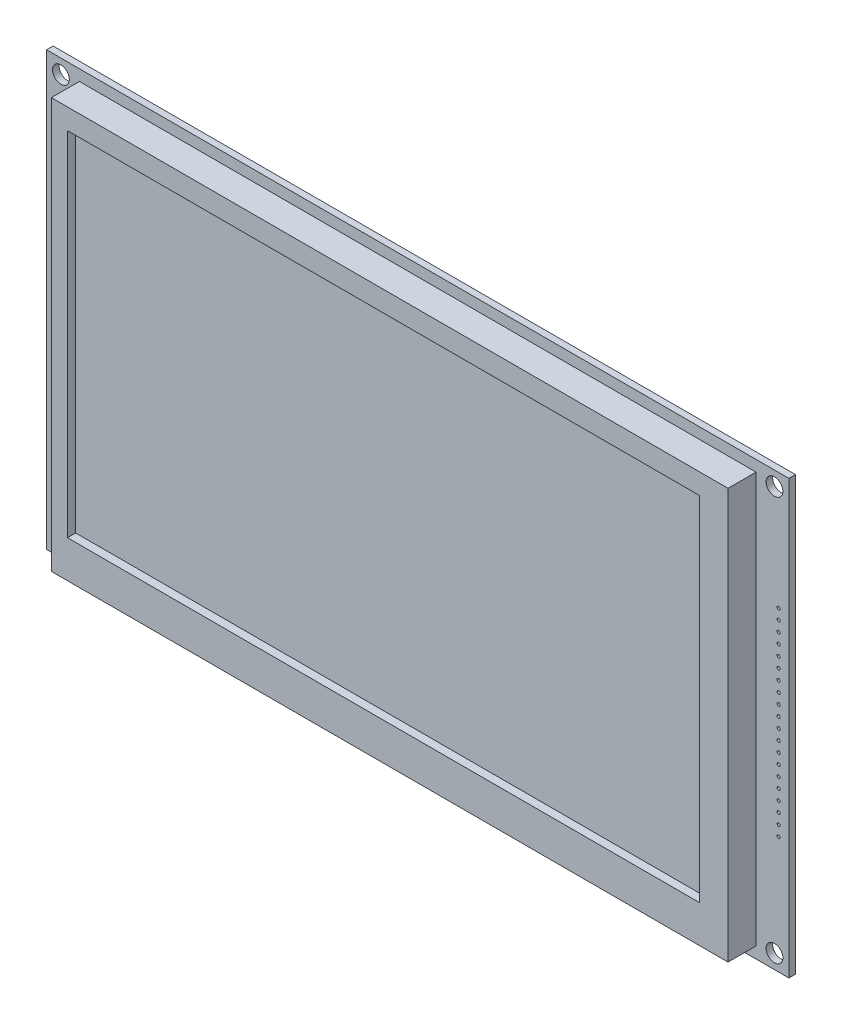
SolidWorks part; units mm, degrees
material "Custom Plastic"
ref_plane "Front Plane" through (0, 0, 0) normal (0, 0, 1) x (1, 0, 0)
ref_plane "Top Plane" through (0, 0, 0) normal (0, 1, 0) x (1, 0, 0)
ref_plane "Right Plane" through (0, 0, 0) normal (1, 0, 0) x (0, 0, -1)
sketch "Sketch1" plane through (0, 0, 0) normal (0, 0, 1) x (1, 0, 0)
  line L1 (90.45, -52.725) -> (-90.45, -52.725)
  line L2 (90.45, -52.725) -> (90.45, 52.725)
  line L3 (90.45, 52.725) -> (-90.45, 52.725)
  line L4 (-90.45, -52.725) -> (-90.45, 52.725)
  line L5 (90.45, -52.725) -> (-90.45, 52.725) construction
  line L6 (90.45, 52.725) -> (-90.45, -52.725) construction
  circle A0 centre (86.95, 49.245) radius 2.05
  circle A1 centre (-86.96, 49.245) radius 2.05
  circle A2 centre (-86.96, -49.225) radius 2.05
  circle A3 centre (86.95, -49.225) radius 2.05
  point P0 (0, 0)
  dimension "D3" = 4.1
  dimension "D4" = 3.5
  dimension "D7" = 3.48
  dimension "D8" = 98.47
  dimension "D1" = 105.45
  dimension "D2" = 180.9
  dimension "D6" = 173.91
extrude "Boss-Extrude1" add sketch "Sketch1" along normal mid plane 1.6
sketch "Sketch2" plane through (0, 0, 0.8) normal (0, 0, 1) x (1, 0, 0)
  line L0 (90.45, 52.725) -> (-90.45, 52.725) construction
  line L1 (-82.45, 50.045) -> (82.45, 50.045)
  line L2 (-82.45, 50.045) -> (-82.45, -49.955)
  line L3 (-82.45, -49.955) -> (82.45, -49.955)
  line L4 (82.45, 50.045) -> (82.45, -49.955)
  line L5 (90.45, -52.725) -> (90.45, 52.725) construction
  dimension "D1" = 164.9
  dimension "D2" = 100
  dimension "D3" = 2.68
  dimension "D4" = 8
extrude "Boss-Extrude2" add sketch "Sketch2" along normal blind 6.83
sketch "Sketch3" plane through (0, -52.725, 0) normal (0, -1, 0) x (1, 0, 0)
  line L0 (17.37, -0.8) -> (23.15, -0.8)
  line L1 (-0.91, -0.8) -> (4.87, -0.8)
  line L2 (-2.49, -2.38) -> (-2.49, -2.48)
  line L3 (-0.91, -4.06) -> (4.87, -4.06)
  line L4 (6.45, -2.38) -> (6.45, -2.48)
  line L5 (15.79, -2.38) -> (15.79, -2.48)
  line L6 (17.37, -4.06) -> (23.15, -4.06)
  line L7 (24.73, -2.38) -> (24.73, -2.48)
  line L8 (-90.45, -0.8) -> (90.45, -0.8) construction
  line L9 (-90.45, 0.8) -> (-90.45, -0.8) construction
  arc A0 (4.87, -0.8) -> (6.45, -2.38) centre (4.87, -2.38) cw
  arc A1 (4.87, -4.06) -> (6.45, -2.48) centre (4.87, -2.48) ccw
  arc A2 (-2.49, -2.48) -> (-0.91, -4.06) centre (-0.91, -2.48) ccw
  arc A3 (-0.91, -0.8) -> (-2.49, -2.38) centre (-0.91, -2.38) ccw
  arc A4 (15.79, -2.48) -> (17.37, -4.06) centre (17.37, -2.48) ccw
  arc A5 (17.37, -0.8) -> (15.79, -2.38) centre (17.37, -2.38) ccw
  arc A6 (23.15, -0.8) -> (24.73, -2.38) centre (23.15, -2.38) cw
  arc A7 (23.15, -4.06) -> (24.73, -2.48) centre (23.15, -2.48) ccw
  point P14 (1.98, -4.06)
  point P15 (20.26, -4.06)
  point P20 (6.45, -4.06)
  point P23 (-2.49, -4.06)
  point P26 (-2.49, -0.8)
  dimension "D5" = 1.58
  dimension "D1" = 8.94
  dimension "D2" = 3.26
  dimension "D3" = 92.43
  dimension "D4" = 110.71
extrude "Boss-Extrude3" add sketch "Sketch3" against normal blind 11
sketch "Sketch4" plane through (0, 0, -0.8) normal (0, 0, -1) x (-1, 0, 0)
  line L0 (90.45, -52.725) -> (0.91, -52.725) construction
  line L1 (62.92, -52.205) -> (69.92, -52.205)
  line L2 (62.92, -52.205) -> (62.92, -48.205)
  line L3 (62.92, -48.205) -> (69.92, -48.205)
  line L4 (69.92, -52.205) -> (69.92, -48.205)
  line L5 (62.92, -52.205) -> (69.92, -48.205) construction
  line L6 (62.92, -48.205) -> (69.92, -52.205) construction
  line L7 (73.41, -52.205) -> (80.41, -52.205)
  line L8 (73.41, -52.205) -> (73.41, -48.205)
  line L9 (73.41, -48.205) -> (80.41, -48.205)
  line L10 (80.41, -52.205) -> (80.41, -48.205)
  line L11 (73.41, -52.205) -> (80.41, -48.205) construction
  line L12 (73.41, -48.205) -> (80.41, -52.205) construction
  line L13 (90.45, 52.725) -> (90.45, -52.725) construction
  point P0 (66.42, -50.205)
  point P5 (76.91, -50.205)
  dimension "D1" = 7
  dimension "D2" = 2.52
  dimension "D3" = 13.54
  dimension "D4" = 24.03
  dimension "D5" = 4
extrude "Boss-Extrude4" add sketch "Sketch4" along normal blind 1.5
sketch "Sketch5" plane through (0, 0, -0.8) normal (0, 0, -1) x (-1, 0, 0)
  line L5 (90.45, 52.725) -> (90.45, -52.725) construction
  line L6 (-90.45, -52.725) -> (-90.45, 52.725) construction
  circle A0 centre (87.95, 24.125) radius 0.38
  circle A1 centre (86.96, 49.245) radius 2.05 construction
  circle A2 centre (87.95, 21.585) radius 0.38
  circle A3 centre (87.95, 19.045) radius 0.38
  circle A4 centre (87.95, 16.505) radius 0.38
  circle A5 centre (87.95, 13.965) radius 0.38
  circle A6 centre (87.95, 11.425) radius 0.38
  circle A7 centre (87.95, 8.885) radius 0.38
  circle A8 centre (87.95, 6.345) radius 0.38
  circle A9 centre (87.95, 3.805) radius 0.38
  circle A10 centre (87.95, 1.265) radius 0.38
  circle A11 centre (87.95, -1.275) radius 0.38
  circle A12 centre (87.95, -3.815) radius 0.38
  circle A13 centre (87.95, -6.355) radius 0.38
  circle A14 centre (87.95, -8.895) radius 0.38
  circle A15 centre (87.95, -11.435) radius 0.38
  circle A16 centre (87.95, -13.975) radius 0.38
  circle A17 centre (87.95, -16.515) radius 0.38
  circle A18 centre (87.95, -19.055) radius 0.38
  circle A19 centre (87.95, -21.595) radius 0.38
  circle A20 centre (87.95, -24.135) radius 0.38
  circle A21 centre (-87.96, 24.095) radius 0.38
  circle A22 centre (-86.95, 49.245) radius 2.05 construction
  circle A23 centre (-87.96, 21.555) radius 0.38
  circle A24 centre (-87.96, 19.015) radius 0.38
  circle A25 centre (-87.96, 16.475) radius 0.38
  circle A26 centre (-87.96, 13.935) radius 0.38
  circle A27 centre (-87.96, 11.395) radius 0.38
  circle A28 centre (-87.96, 8.855) radius 0.38
  circle A29 centre (-87.96, 6.315) radius 0.38
  circle A30 centre (-87.96, 3.775) radius 0.38
  circle A31 centre (-87.96, 1.235) radius 0.38
  circle A32 centre (-87.96, -1.305) radius 0.38
  circle A33 centre (-87.96, -3.845) radius 0.38
  circle A34 centre (-87.96, -6.385) radius 0.38
  circle A35 centre (-87.96, -8.925) radius 0.38
  circle A36 centre (-87.96, -11.465) radius 0.38
  circle A37 centre (-87.96, -14.005) radius 0.38
  circle A38 centre (-87.96, -16.545) radius 0.38
  circle A39 centre (-87.96, -19.085) radius 0.38
  circle A40 centre (-87.96, -21.625) radius 0.38
  circle A41 centre (-87.96, -24.165) radius 0.38
  dimension "D1" = 0.76
  dimension "D2" = 25.12
  dimension "D5" = 25.15
  dimension "D6" = 2.49
  dimension "D3" = 2.5
  dimension "D4" = 20
  dimension "D7" = 20
extrude "Cut-Extrude1" cut sketch "Sketch5" against normal through all both and the other way through all
sketch "Sketch6" plane through (0, 0, 7.63) normal (0, 0, 1) x (1, 0, 0)
  line L1 (-78.52, 45.045) -> (75.56, 45.045)
  line L2 (-78.52, 45.045) -> (-78.52, -40.875)
  line L3 (-78.52, -40.875) -> (75.56, -40.875)
  line L4 (75.56, 45.045) -> (75.56, -40.875)
  line L5 (90.45, -52.725) -> (90.45, 52.725) construction
  line L6 (90.45, 52.725) -> (-90.45, 52.725) construction
  dimension "D1" = 85.92
  dimension "D2" = 154.08
  dimension "D3" = 7.68
  dimension "D4" = 14.89
extrude "Cut-Extrude2" cut sketch "Sketch6" against normal blind 2
